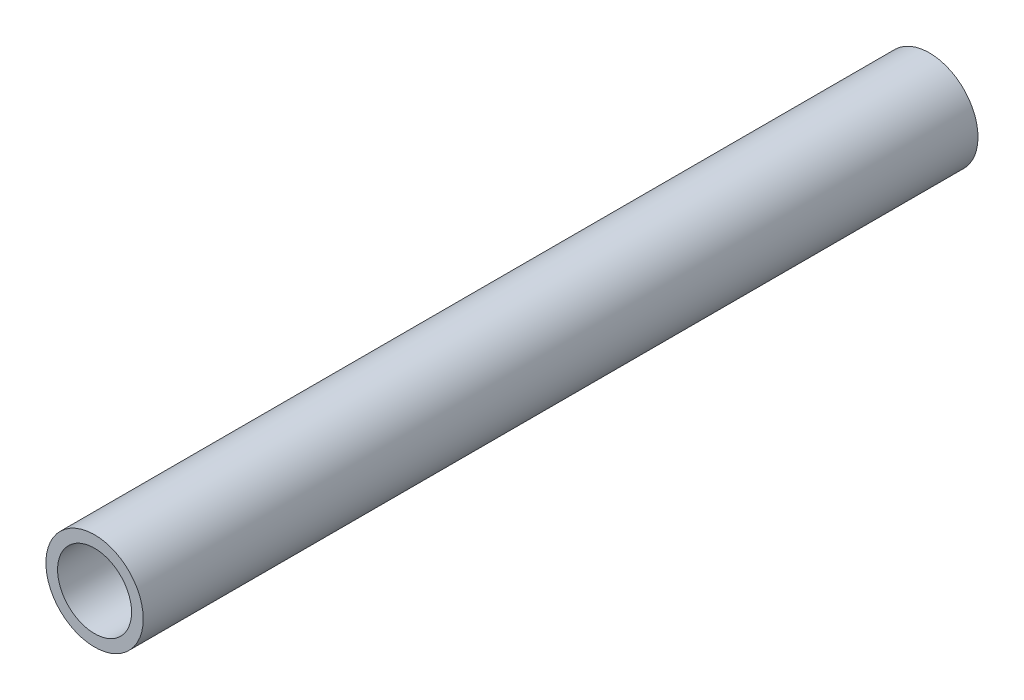
SolidWorks part; units mm, degrees
material "Plain Carbon Steel"
ref_plane "Front Plane" through (0, 0, 0) normal (0, 0, 1) x (1, 0, 0)
ref_plane "Top Plane" through (0, 0, 0) normal (0, 1, 0) x (1, 0, 0)
ref_plane "Right Plane" through (0, 0, 0) normal (1, 0, 0) x (0, 0, -1)
sketch3d "3DSketch1"
  line L0 (0, 0, 0) -> (0, 0, 286.512)
sketch "Sketch2" plane through (0, 0, 0) normal (0, 0, 1) x (1, 0, 0)
  circle A0 centre (0, 0) radius 16.7005
extrude "Extrude-Thin1" add sketch "Sketch2" along normal blind 286.512 thin thin type one direction reverse wall 4.0005
